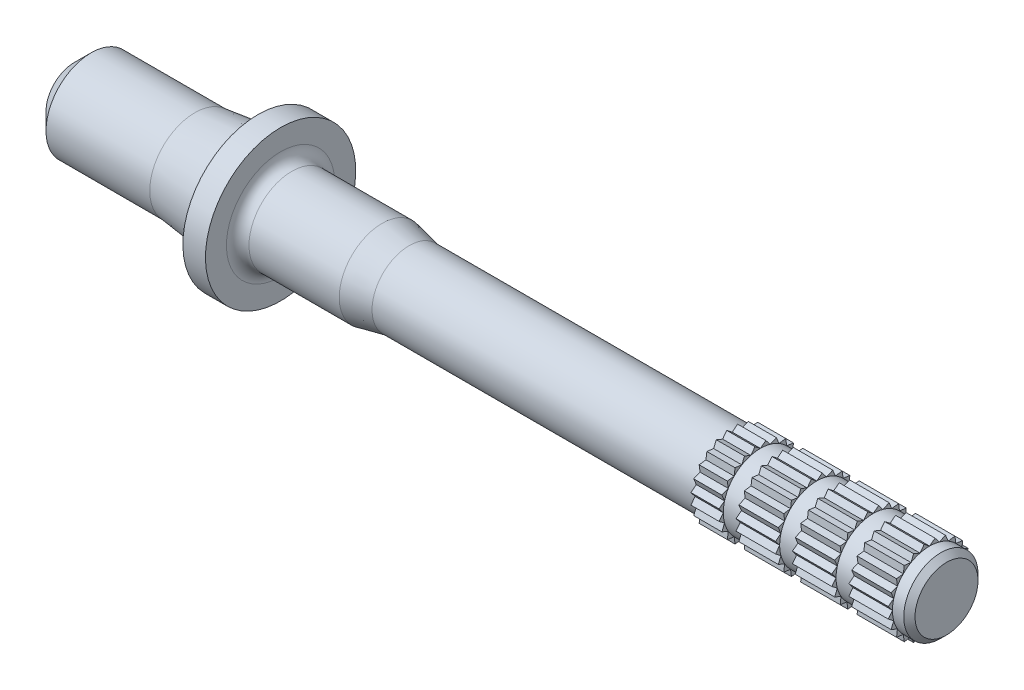
SolidWorks part; units mm, degrees
ref_plane "Front Plane" through (0, 0, 0) normal (0, 0, 1) x (1, 0, 0)
ref_plane "Top Plane" through (0, 0, 0) normal (0, 1, 0) x (1, 0, 0)
ref_plane "Right Plane" through (0, 0, 0) normal (1, 0, 0) x (0, 0, -1)
sketch "Sketch1" plane through (0, 0, 0) normal (0, 0, 1) x (1, 0, 0)
  line L0 (0, 0) -> (0, 2)
  line L1 (0, 2) -> (5.35, 2)
  line L2 (5.35, 2) -> (8.15, 2.3314)
  line L3 (8.15, 2.3314) -> (8.15, 3.3314)
  line L4 (8.15, 3.3314) -> (9.15, 3.3314)
  line L5 (9.15, 3.3314) -> (9.15, 1.9014)
  line L6 (9.15, 1.9014) -> (13.65, 1.9014)
  line L7 (13.65, 1.9014) -> (14.85, 1.6463)
  line L8 (14.85, 1.6463) -> (29.17, 1.6463)
  line L9 (29.17, 1.6463) -> (29.17, 1.85)
  line L10 (29.17, 1.85) -> (38.67, 1.85)
  line L11 (38.67, 1.85) -> (38.67, 0)
  line L12 (38.67, 0) -> (0, 0)
  dimension "D1" = 2
  dimension "D2" = 5.35
  dimension "D3" = 2.8
  dimension "D4" = 173.25
  dimension "D5" = 1
  dimension "D6" = 1
  dimension "D7" = 1.43
  dimension "D8" = 168
  dimension "D9" = 1.2
  dimension "D10" = 4.5
  dimension "D11" = 14.32
  dimension "D12" = 9.5
  dimension "D13" = 1.85
  dimension "D14" = 0.2037
revolve "Revolve1" add sketch "Sketch1" angle 360 about L12
sketch "Sketch2" plane through (38.67, 0, 0) normal (1, 0, 0) x (0, 0, -1)
  line L0 (0, 0) -> (0, 1.9014) construction
  line L1 (-0.2443, 1.8338) -> (0, 1.6463)
  line L2 (0, 1.6463) -> (0.2443, 1.8338)
  circle A0 centre (0, 0) radius 1.9014 construction
  circle A1 centre (0, 0) radius 1.6463 construction
  circle A2 centre (0, 0) radius 1.85 construction
  arc A3 (-0.2443, 1.8338) -> (0.2443, 1.8338) centre (0, 0) cw
  dimension "D1" = 105
extrude "Cut-Extrude1" cut sketch "Sketch2" against normal up to next
pattern_circular "CirPattern1" count 24 over 360 about axis through (0, 0, 0) along (1, 0, 0) of "Cut-Extrude1"
sketch "Sketch3" plane through (38.67, 0, 0) normal (1, 0, 0) x (0, 0, -1)
  circle A0 centre (0, 0) radius 1.6463
extrude "Cut-Extrude2" cut sketch "Sketch3" against normal blind 0.75 flip side to cut
pattern_linear "LPattern1" count 4 spacing 2.5 along (-1, 0, 0) of "Cut-Extrude2"
chamfer "Chamfer1" distance 0.75 angle 45 1 edges at (0, 2, 0)
chamfer "Chamfer2" distance 0.25 angle 45 1 edges at (38.67, 1.6463, 0)
fillet "Fillet1" radius 0.5 2 edges at (8.15, 2.3314, 0) (9.15, 1.9014, 0)
